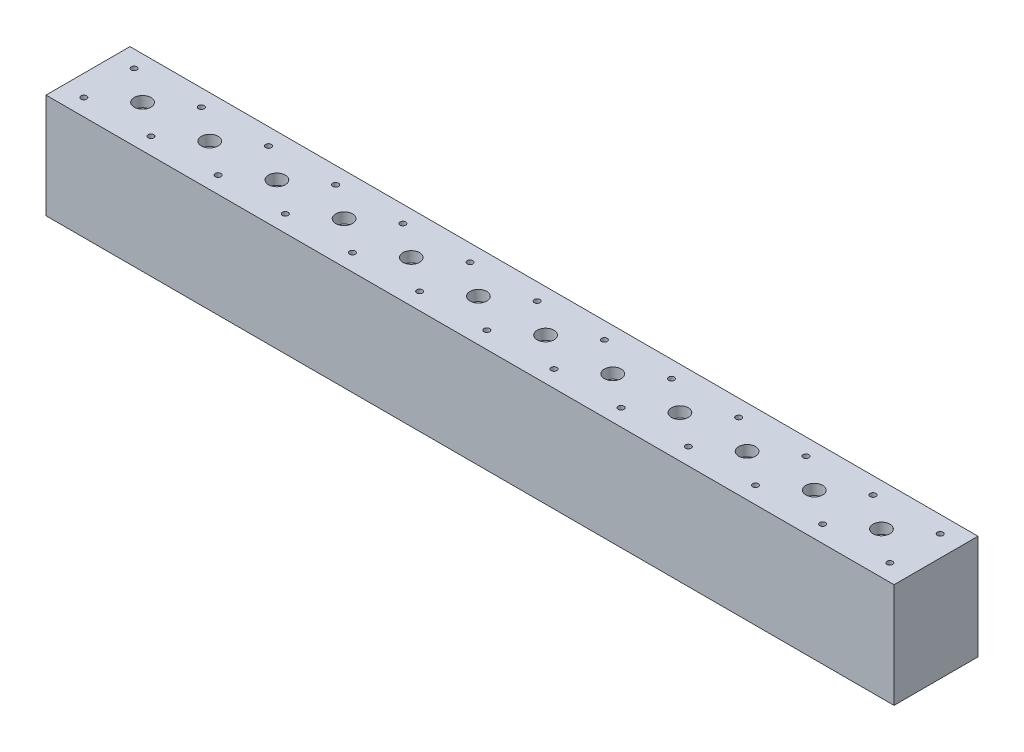
SolidWorks part; units mm, degrees
material "Plain Carbon Steel"
ref_plane "Front Plane" through (0, 0, 0) normal (0, 0, 1) x (1, 0, 0)
ref_plane "Top Plane" through (0, 0, 0) normal (0, 1, 0) x (1, 0, 0)
ref_plane "Right Plane" through (0, 0, 0) normal (1, 0, 0) x (0, 0, -1)
sketch "Sketch1" plane through (0, 0, 0) normal (1, 0, 0) x (0, 0, -1)
  line L1 (-50, -62.25) -> (50, -62.25)
  line L2 (-50, -62.25) -> (-50, 62.25)
  line L3 (-50, 62.25) -> (50, 62.25)
  line L4 (50, -62.25) -> (50, 62.25)
  line L5 (-50, -62.25) -> (50, 62.25) construction
  line L6 (-50, 62.25) -> (50, -62.25) construction
  point P0 (0, 0)
  dimension "D1" = 100
  dimension "D2" = 124.5
extrude "Boss-Extrude1" add sketch "Sketch1" along normal mid plane 1010
hole_wizard "M8 Tapped Hole1" positions "Sketch4" profile "Sketch3" tap size "M8" standard "ISO"
sketch "Sketch4" plane through (0, 62.25, 0) normal (0, 1, 0) x (1, 0, 0)
  point P0 (480, 30)
  point P3 (480, -30)
  point P6 (400, 30)
  point P9 (400, -30)
  point P12 (320, 30)
  point P15 (320, -30)
  point P18 (240, -30)
  point P21 (240, 30)
  point P24 (160, 30)
  point P27 (160, -30)
  point P30 (80, 30)
  point P33 (80, -30)
  point P36 (0, -30)
  point P39 (0, 30)
  point P42 (-80, -30)
  point P45 (-80, 30)
  point P48 (-160, -30)
  point P51 (-160, 30)
  point P54 (-240, -30)
  point P57 (-240, 30)
  point P60 (-320, -30)
  point P63 (-320, 30)
  point P66 (-400, -30)
  point P69 (-400, 30)
  point P72 (-480, 30)
  point P75 (-480, -30)
sketch "Sketch3" plane through (480, 62.25, -30) normal (1, 0, 0) x (0, 0, 1)
  line L0 (0, 0) -> (0, 24.2929)
  line L1 (0, 24.2929) -> (3.4, 22.25)
  line L2 (3.4, 22.25) -> (3.4, 0)
  line L5 (3.4, 0) -> (0, 0)
  line L10 (0, 24.2929) -> (-3.4, 22.25) construction
  line L11 (0, -6.35) -> (0, 107.95) construction
  dimension "Tap Drill Dia." = 6.8
  dimension "Tap Drill Depth" = 22.25
  dimension "Drill Angle" = 118
cosmetic thread "Hole Thread1" parameters "D1"=16, "D2"=8
cosmetic thread "Hole Thread2" parameters "D1"=16, "D2"=8
cosmetic thread "Hole Thread3" parameters "D1"=16, "D2"=8
cosmetic thread "Hole Thread4" parameters "D1"=16, "D2"=8
cosmetic thread "Hole Thread5" parameters "D1"=16, "D2"=8
cosmetic thread "Hole Thread6" parameters "D1"=16, "D2"=8
cosmetic thread "Hole Thread7" parameters "D1"=16, "D2"=8
cosmetic thread "Hole Thread8" parameters "D1"=16, "D2"=8
cosmetic thread "Hole Thread9" parameters "D1"=16, "D2"=8
cosmetic thread "Hole Thread10" parameters "D1"=16, "D2"=8
cosmetic thread "Hole Thread11" parameters "D1"=16, "D2"=8
cosmetic thread "Hole Thread12" parameters "D1"=16, "D2"=8
cosmetic thread "Hole Thread13" parameters "D1"=16, "D2"=8
cosmetic thread "Hole Thread14" parameters "D1"=16, "D2"=8
cosmetic thread "Hole Thread15" parameters "D1"=16, "D2"=8
cosmetic thread "Hole Thread16" parameters "D1"=16, "D2"=8
cosmetic thread "Hole Thread17" parameters "D1"=16, "D2"=8
cosmetic thread "Hole Thread18" parameters "D1"=16, "D2"=8
cosmetic thread "Hole Thread19" parameters "D1"=16, "D2"=8
cosmetic thread "Hole Thread20" parameters "D1"=16, "D2"=8
cosmetic thread "Hole Thread21" parameters "D1"=16, "D2"=8
cosmetic thread "Hole Thread22" parameters "D1"=16, "D2"=8
cosmetic thread "Hole Thread23" parameters "D1"=16, "D2"=8
cosmetic thread "Hole Thread24" parameters "D1"=16, "D2"=8
cosmetic thread "Hole Thread25" parameters "D1"=16, "D2"=8
cosmetic thread "Hole Thread26" parameters "D1"=16, "D2"=8
sketch "Sketch7" plane through (0, 62.25, 0) normal (0, 1, 0) x (1, 0, 0)
  line L0 (400, 30) -> (480, 30) construction
  line L2 (400, -30) -> (480, -30) construction
  line L4 (440, -30) -> (440, 30) construction
  point P0 (440, 0)
  point P19 (440, 0)
hole_wizard "CBORE for M12 Hex Socket Head Cap Screw1" positions "Sketch7" profile "Sketch6" counterbore size "M12" standard "ISO" end condition through all
sketch "Sketch6" plane through (440, 62.25, 0) normal (1, 0, 0) x (0, 0, 1)
  line L0 (0, 0) -> (0, 124.5)
  line L1 (0, 124.5) -> (6.5, 124.5)
  line L3 (6.5, 124.5) -> (6.5, 12.6)
  line L4 (6.5, 12.6) -> (10, 12.6)
  line L5 (10, 12.6) -> (10, 0)
  line L7 (10, 0) -> (0, 0)
  line L11 (0, -6.35) -> (0, 107.95) construction
  dimension "Thru Hole Dia." = 13
  dimension "Thru Hole Depth" = 124.5
  dimension "C'Bore Dia." = 20
  dimension "C'Bore Depth" = 12.6
pattern_linear "LPattern1" count 12 spacing 80 along (-1, 0, 0) of "CBORE for M12 Hex Socket Head Cap Screw1"
